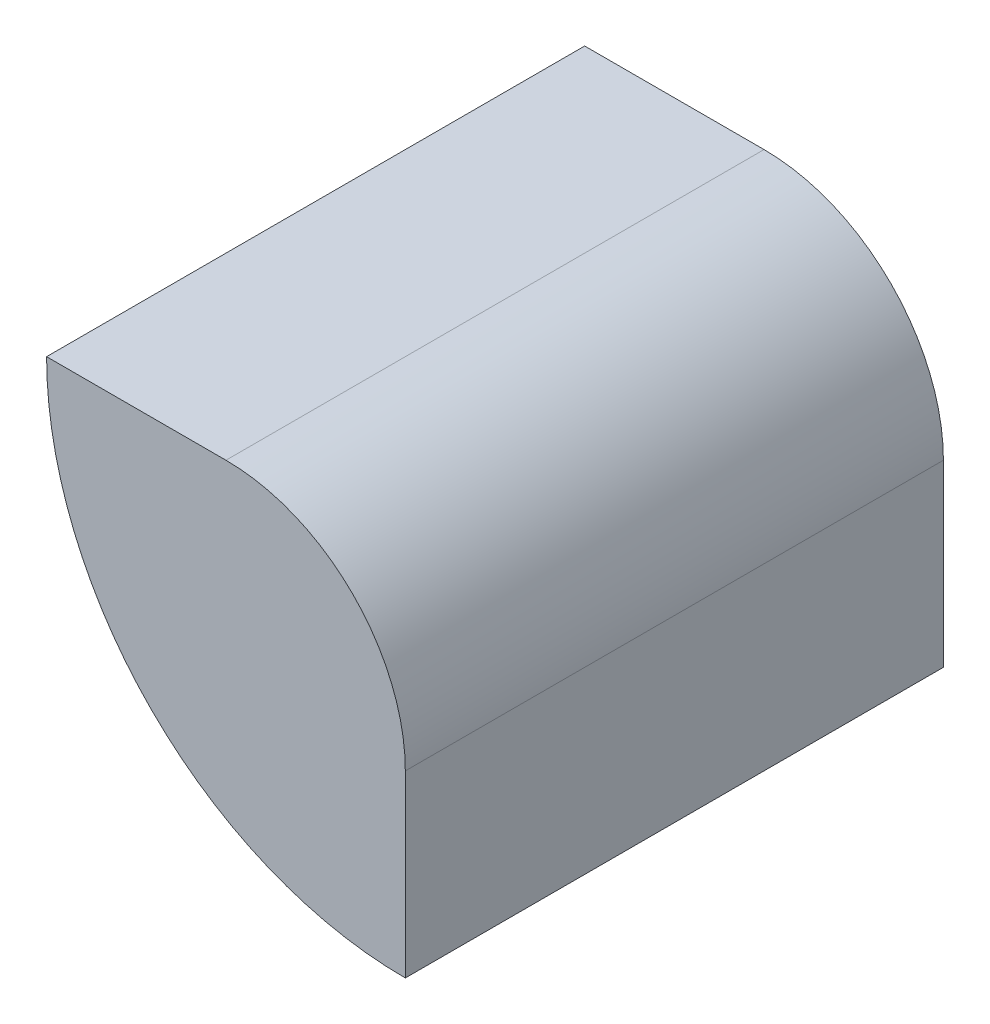
SolidWorks part; units mm, degrees
ref_plane "Plano frontal" through (0, 0, 0) normal (0, 0, 1) x (1, 0, 0)
ref_plane "Plano superior" through (0, 0, 0) normal (0, 1, 0) x (1, 0, 0)
ref_plane "Plano direito" through (0, 0, 0) normal (1, 0, 0) x (0, 0, -1)
sketch "Esboço1" plane through (0, 0, 0) normal (0, 0, 1) x (1, 0, 0)
  line L0 (-43.3361, -36.9754) -> (-43.3361, -31.9754)
  line L1 (-53.3361, -26.9754) -> (-48.3361, -26.9754)
  arc A0 (-43.3361, -31.9754) -> (-48.3361, -26.9754) centre (-48.3361, -31.9754) ccw
  arc A2 (-53.3361, -26.9754) -> (-43.3361, -36.9754) centre (-43.3361, -26.9754) ccw
  dimension "D1" = 5
extrude "Ressalto-extrusão1" add sketch "Esboço1" along normal blind 15 contours A0 L1 A2 L0
